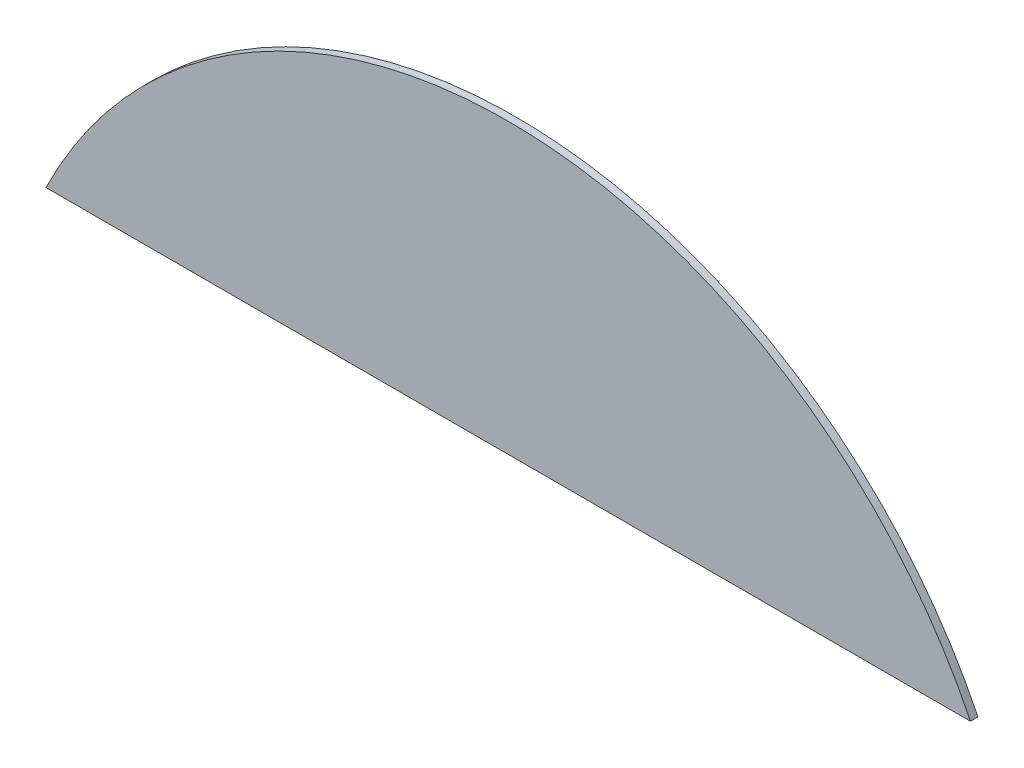
SolidWorks part; units mm, degrees
ref_plane "前视基准面" through (0, 0, 0) normal (0, 0, 1) x (1, 0, 0)
ref_plane "上视基准面" through (0, 0, 0) normal (0, 1, 0) x (1, 0, 0)
ref_plane "右视基准面" through (0, 0, 0) normal (1, 0, 0) x (0, 0, -1)
sketch "草图1" plane through (0, 0, 0) normal (0, 0, 1) x (1, 0, 0)
  arc A0 (-203, 0) -> (203, 0) centre (0, 0) ccw
  arc A1 (-210, 0) -> (210, 0) centre (0, 0) ccw
  arc A2 (-203, 0) -> (203, 0) centre (0, 0) ccw
  circle A3 centre (0, 0) radius 210
  circle A4 centre (0, 0) radius 203
  point P12 (0, 0)
extrude "凸台-拉伸2" add sketch "草图1" along normal blind 174
sketch "草图2" plane through (0, 0, 174) normal (0, 0, 1) x (1, 0, 0)
  line L0 (-173.7354, -102) -> (-170.7354, -102)
  line L1 (-170.7354, -102) -> (-170.7354, -105)
  line L2 (-170.7354, -105) -> (-173.7354, -105)
  line L3 (173.7354, -102) -> (170.7354, -102)
  line L4 (-173.7354, -102) -> (-175.5135, -102)
  line L6 (173.7354, -102) -> (175.5135, -102)
  line L7 (173.7354, -105) -> (170.7354, -105)
  line L8 (170.7354, -105) -> (170.7354, -102)
  circle A0 centre (0, 0) radius 203 construction
  arc A1 (0, -203) -> (-173.7354, -105) centre (0, 0) ccw
  circle M4 centre (0, 0) radius 203
extrude "凸台-拉伸4" add sketch "草图2" against normal up to surface (174 mm away) contours L0 L4 L2 L1 M4 | L8 L7 L6 L3 M4 up to face at (203, 0, 0)
sketch "草图3" plane through (0, 0, 174) normal (0, 0, 1) x (1, 0, 0)
  line L0 (-170.7354, -102) -> (238.3336, -102)
  line L1 (238.3336, -102) -> (254.3342, 272.2925)
  line L2 (254.3342, 272.2925) -> (-334.5694, 221.8511)
  line L3 (-170.7354, -102) -> (-306.8306, -102)
  line L4 (-306.8306, -102) -> (-334.5694, 221.8511)
extrude "切除-拉伸1" cut sketch "草图3" against normal blind 654
ref_plane "基准面1" through (0, -209.75, 0) normal (0, 1, 0) x (1, 0, 0)
sketch "草图5" plane through (0, 0, 174) normal (0, 0, 1) x (1, 0, 0)
  line L0 (0, -209.75) -> (120, -209.75)
  line L1 (95.7, -209.75) -> (-95.7, -209.75) construction
  line L2 (120, -209.75) -> (120, -172.0322)
  line L3 (0, -209.75) -> (-120, -209.75)
  line L4 (-120, -209.75) -> (-120, -172.0322)
  arc A0 (-120, -172.0322) -> (120, -172.0322) centre (0, 0) ccw
  arc M3 (-183.5647, -102) -> (183.5647, -102) centre (0, 0) ccw
extrude "凸台-拉伸5" add sketch "草图5" against normal up to surface (174 mm away) contours L4 L3 M3 | L0 L2 M3 up to face at (0, -129.25, 0)
sketch "草图6" plane through (0, 0, 174) normal (0, 0, 1) x (1, 0, 0)
  line L0 (-175.5135, -102) -> (-166.1957, -102)
  line L1 (175.5135, -102) -> (166.1957, -102)
  arc A0 (-166.1957, -102) -> (166.1957, -102) centre (0, 0) ccw
  arc A1 (-175.5135, -102) -> (175.5135, -102) centre (0, 0) ccw
extrude "凸台-拉伸6" add sketch "草图6" against normal up to surface (174 mm away) up to face at (0, -151.228, 0)
sketch "草图7" plane through (0, 0, 174) normal (0, 0, 1) x (1, 0, 0)
  line L0 (-166.9331, -92) -> (-166.9331, -95)
  line L1 (171.9331, -92) -> (166.9331, -92)
  line L2 (-171.9331, -92) -> (-166.9331, -92)
  line L3 (-188.4969, -92) -> (-171.9331, -92)
  line L4 (171.9331, -92) -> (188.4969, -92)
  line L5 (-166.9331, -95) -> (-170.2939, -95)
  line L6 (166.9331, -92) -> (166.9331, -95)
  line L7 (166.9331, -95) -> (170.2939, -95)
  arc A1 (-188.4969, -92) -> (188.4969, -92) centre (0, 0) ccw
  arc A2 (-170.2939, -95) -> (170.2939, -95) centre (0, 0) ccw
extrude "凸台-拉伸7" add sketch "草图7" against normal up to surface (174 mm away) up to face at (0, -169.2192, 0)
sketch "草图8" plane through (0, 0, 0) normal (0, 0, -1) x (-1, 0, 0)
  line L0 (166.9331, -92) -> (163.9331, -92)
  line L1 (163.9331, -92) -> (163.9331, -99)
  line L2 (163.9331, -99) -> (168, -99)
  line L3 (166.9331, -92) -> (166.9331, -95)
  line L4 (166.9331, -95) -> (170.2939, -95)
  line L6 (-166.9331, -95) -> (-170.2939, -95)
  line L7 (-166.9331, -92) -> (-166.9331, -95)
  line L8 (-163.9331, -99) -> (-168, -99)
  line L9 (-163.9331, -92) -> (-163.9331, -99)
  line L10 (-166.9331, -92) -> (-163.9331, -92)
  arc A0 (-170.2939, -95) -> (170.2939, -95) centre (0, 0) ccw construction
  arc A1 (168, -99) -> (170.2939, -95) centre (0, 0) ccw
  arc A2 (-168, -99) -> (-170.2939, -95) centre (0, 0) cw
extrude "凸台-拉伸8" add sketch "草图8" against normal up to surface (174 mm away) up to face at (0, -135.959, 174)
sketch "草图9" plane through (0, 0, 174) normal (0, 0, 1) x (1, 0, 0)
  line L0 (0, 0) -> (0, -337.2155)
  line L3 (-50, -195) -> (-50, -209.75)
  line L4 (-10.2439, -209.75) -> (-120, -209.75) construction
  line L5 (-50, -209.75) -> (50, -209.75)
  line L6 (10.2439, -209.75) -> (120, -209.75) construction
  line L7 (50, -209.75) -> (50, -195)
  line L8 (-50, -195) -> (-50, -182.2253)
  line L9 (-50, -182.2253) -> (50, -182.2253)
  line L10 (50, -182.2253) -> (50, -195)
  arc M4 (168, -99) -> (-168, -99) centre (0, 0) cw
  line M12 (-120, -209.75) -> (-10.2439, -209.75)
  line M14 (10.2439, -209.75) -> (120, -209.75)
extrude "切除-拉伸2" cut sketch "草图9" against normal blind 654 contours L9 L8 L0 M4 | L8 L3 L5 L0 M12 M4 | L10 L0 L5 L7 M4 M14 | L10 L9 L0 M4
sketch "草图10" plane through (0, -209.75, 0) normal (0, 1, 0) x (1, 0, 0)
  line L1 (-10.2439, 0) -> (10.2439, 0)
  line L2 (-10.2439, 0) -> (-10.2439, -174)
  line L3 (-10.2439, -174) -> (10.2439, -174)
  line L4 (10.2439, 0) -> (10.2439, -174)
extrude "切除-拉伸3" cut sketch "草图10" against normal mid plane 654
sketch "草图11" plane through (0, 0, 0) normal (0, 0, -1) x (-1, 0, 0)
  line L1 (18.7676, -16.6345) -> (254.4053, -16.6345)
  line L2 (18.7676, -16.6345) -> (18.7676, -265.8266)
  line L3 (18.7676, -265.8266) -> (254.4053, -265.8266)
  line L4 (254.4053, -16.6345) -> (254.4053, -265.8266)
extrude "切除-拉伸4" cut sketch "草图11" against normal blind 238
ref_plane "基准面2" through (0, 0, 209.75) normal (0, 0, 1) x (1, 0, 0)
sketch "草图14" plane through (0, 0, 209.75) normal (0, 0, 1) x (1, 0, 0)
  line L0 (188.4969, -92) -> (183.1966, -92)
  line L1 (0, 210) -> (0, 205)
  line L2 (183.1966, -92) -> (188.775, -92)
  arc A0 (183.1966, -92) -> (0, 205) centre (0, 0) ccw
  arc A1 (188.775, -92) -> (0, 210) centre (0, 0) ccw
extrude "凸台-拉伸10" add sketch "草图14" along normal blind 180 separate body contours A0 L1 A1 L2
sketch "草图17" plane through (0, -92, 0) normal (0, 1, 0) x (1, 0, 0)
  line L1 (-19.1853, 5.1617) -> (266.9134, 5.1617)
  line L2 (-19.1853, 5.1617) -> (-19.1853, -186.717)
  line L3 (-19.1853, -186.717) -> (266.9134, -186.717)
  line L4 (266.9134, 5.1617) -> (266.9134, -186.717)
extrude "切除-拉伸5" cut sketch "草图17" against normal blind 322
sketch "草图18" plane through (0, 0, 389.75) normal (0, 0, 1) x (1, 0, 0)
  line L0 (0, 210) -> (0, 205)
  line L1 (188.775, -92) -> (183.1966, -92)
  line L2 (-183.1966, -92) -> (-188.775, -92)
  arc A0 (0, 205) -> (-183.1966, -92) centre (0, 0) ccw
  arc A1 (0, 210) -> (-188.775, -92) centre (0, 0) ccw
  line M3 (0, 210) -> (0, 205)
extrude "凸台-拉伸11" add sketch "草图18" against normal up to surface (180 mm away) contours A1 L2 A0 M3 up to face at (134.6342, 83.6081, 209.75)
sketch "草图19" plane through (0, 0, 389.75) normal (0, 0, 1) x (1, 0, 0)
  line L0 (-188.775, -92) -> (188.775, -92)
  line L1 (0, -92) -> (0, 98)
  line L2 (0, 98) -> (195.9962, 98)
  line L3 (195.9962, 98) -> (-278.828, 98)
sketch "草图20" plane through (0, 0, 0) normal (1, 0, 0) x (0, 0, -1)
  circle A2 centre (-382.75, 98) radius 4
extrude "切除-拉伸7" cut sketch "草图20" against normal mid plane 1111
sketch "草图24" plane through (0, 0, 0) normal (0, 0, 1) x (1, 0, 0)
  line L1 (0, 90) -> (-184.1874, 90)
  line L4 (-184.1874, 90) -> (184.1874, 90)
  arc A0 (178.1175, 101.4848) -> (-178.1175, 101.4848) centre (0, 0) ccw
  arc A1 (184.1874, 90) -> (-184.1874, 90) centre (0, 0) ccw
extrude "凸台-拉伸13" add sketch "草图24" along normal blind 3 separate body
sketch "草图25" plane through (0, 0, 0) normal (0, 1, 0) x (1, 0, 0)
  line L1 (-338.1403, -159.4474) -> (395.6662, -159.4474)
  line L2 (-338.1403, -159.4474) -> (-338.1403, -466.3694)
  line L3 (-338.1403, -466.3694) -> (395.6662, -466.3694)
  line L4 (395.6662, -159.4474) -> (395.6662, -466.3694)
extrude "切除-拉伸8" cut sketch "草图25" against normal mid plane 481
